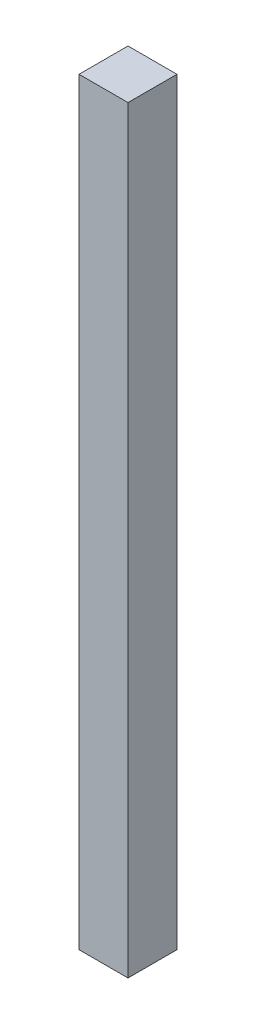
SolidWorks part; units mm, degrees
ref_plane "Front Plane" through (0, 0, 0) normal (0, 0, 1) x (1, 0, 0)
ref_plane "Top Plane" through (0, 0, 0) normal (0, 1, 0) x (1, 0, 0)
ref_plane "Right Plane" through (0, 0, 0) normal (1, 0, 0) x (0, 0, -1)
sketch "Sketch1" plane through (0, 0, 0) normal (0, 1, 0) x (1, 0, 0)
  line L1 (0, 0) -> (25.4, 0)
  line L2 (0, 0) -> (0, 25.4)
  line L3 (0, 25.4) -> (25.4, 25.4)
  line L4 (25.4, 0) -> (25.4, 25.4)
  dimension "D1" = 25.4
extrude "Boss-Extrude1" add sketch "Sketch1" along normal blind 393.2
